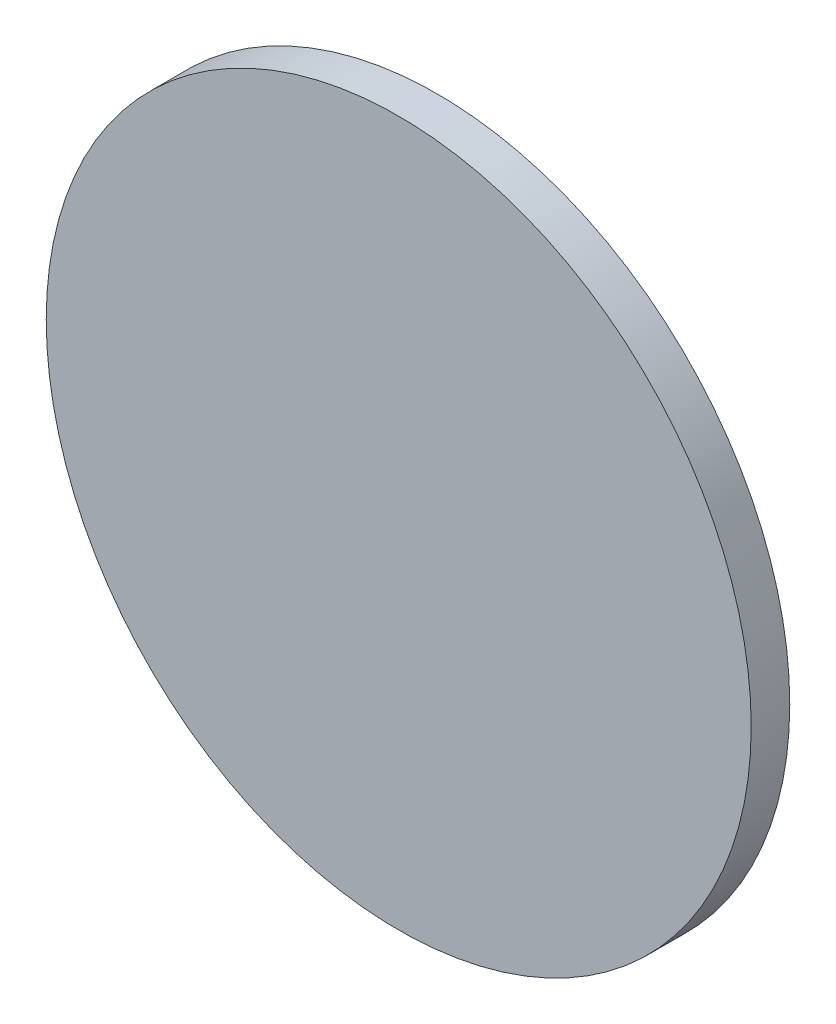
SolidWorks part; units mm, degrees
ref_plane "Front" through (0, 0, 0) normal (0, 0, 1) x (1, 0, 0)
ref_plane "Top" through (0, 0, 0) normal (0, 1, 0) x (1, 0, 0)
ref_plane "Right" through (0, 0, 0) normal (1, 0, 0) x (0, 0, -1)
sketch "草图1" plane through (0, 0, 0) normal (0, 0, 1) x (1, 0, 0)
  circle A0 centre (0, 0) radius 64
  dimension "D1" = 128
extrude "凸台-拉伸1" add sketch "草图1" along normal blind 7
